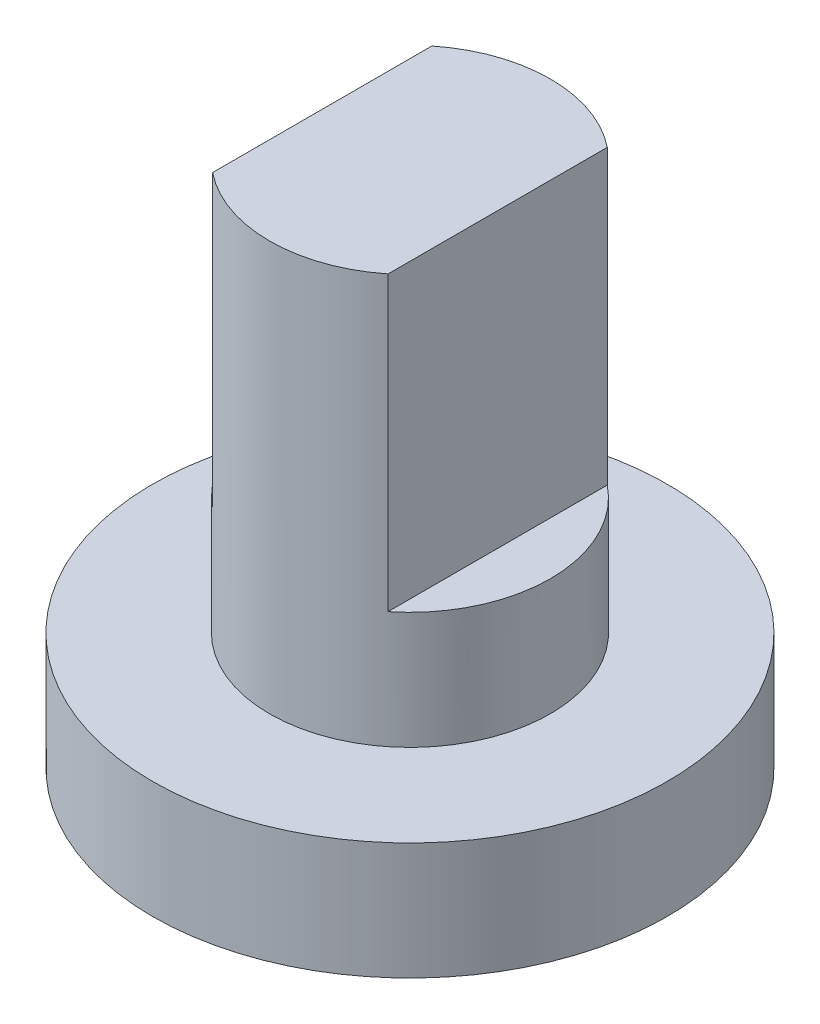
SolidWorks part; units mm, degrees
ref_plane "Front Plane" through (0, 0, 0) normal (0, 0, 1) x (1, 0, 0)
ref_plane "Top Plane" through (0, 0, 0) normal (0, 1, 0) x (1, 0, 0)
ref_plane "Right Plane" through (0, 0, 0) normal (1, 0, 0) x (0, 0, -1)
sketch "Sketch1" plane through (0, 0, 0) normal (0, 1, 0) x (1, 0, 0)
  circle A0 centre (0, 0) radius 4.4
  dimension "D1" = 8.8
extrude "Boss-Extrude1" add sketch "Sketch1" along normal blind 2
sketch "Sketch2" plane through (0, 2, 0) normal (0, 1, 0) x (1, 0, 0)
  circle A0 centre (0, 0) radius 2.4
  dimension "D1" = 4.8
extrude "Boss-Extrude2" add sketch "Sketch2" along normal blind 2
sketch "Sketch3" plane through (0, 4, 0) normal (0, 1, 0) x (1, 0, 0)
  line L2 (-1.5, 1.8735) -> (-1.5, -1.8735)
  line L4 (1.5, 1.8735) -> (1.5, -1.8735)
  line L7 (-1.8735, 1.5) -> (1.8735, 1.5)
  line L9 (-1.8735, -1.5) -> (1.8735, -1.5)
  circle A0 centre (0, 0) radius 2.4
  point P0 (0, 0)
  circle M4 centre (0, 0) radius 2.4
extrude "Boss-Extrude3" add sketch "Sketch3" along normal blind 5 contours L2 L7 L4 M4 | L2 L9 L4 L7 | L9 L2 L4 M4
sketch "Sketch4" plane through (0, 0, 0) normal (0, -1, 0) x (1, 0, 0)
  circle A0 centre (0, 0) radius 2.6
  dimension "D1" = 5.2
